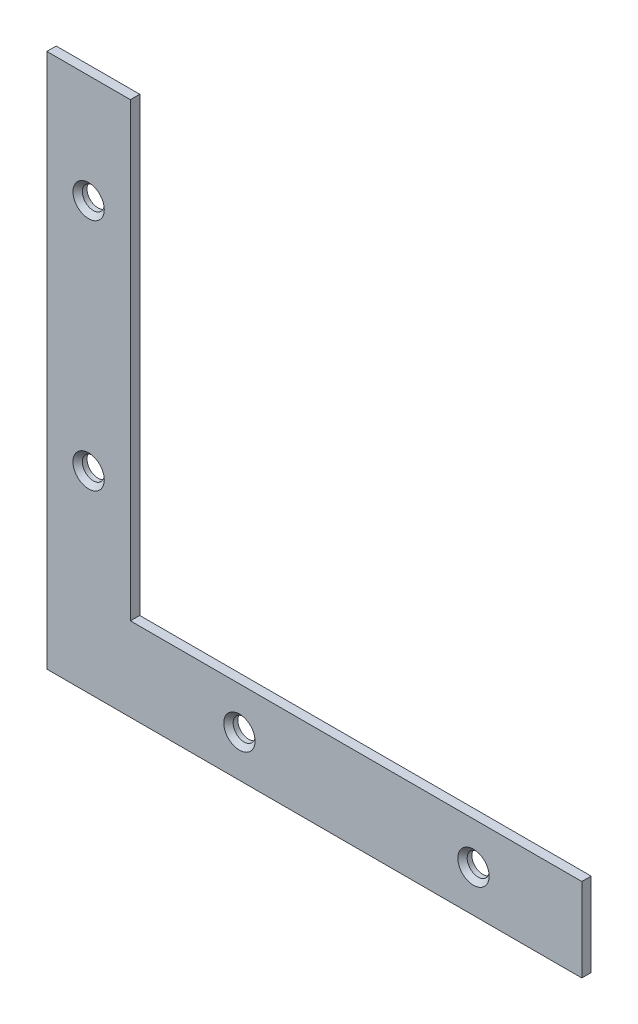
SolidWorks part; units mm, degrees
ref_plane "Front" through (0, 0, 0) normal (0, 0, 1) x (1, 0, 0)
ref_plane "Top" through (0, 0, 0) normal (0, 1, 0) x (1, 0, 0)
ref_plane "Right" through (0, 0, 0) normal (1, 0, 0) x (0, 0, -1)
sketch "Sketch1" plane through (0, 0, 0) normal (0, 0, 1) x (1, 0, 0)
  line L0 (0, 101.6) -> (0, 0)
  line L1 (0, 0) -> (101.6, 0)
  line L2 (101.6, 0) -> (101.6, 15.875)
  line L3 (101.6, 15.875) -> (15.875, 15.875)
  line L4 (15.875, 15.875) -> (15.875, 101.6)
  line L5 (15.875, 101.6) -> (0, 101.6)
  dimension "B" = 15.875
  dimension "A1" = 101.6
extrude "Extrude1" add sketch "Sketch1" along normal mid plane 1.778
sketch "Sketch2" plane through (0, 0, 0) normal (0, 0, 1) x (1, 0, 0)
  line L0 (36.576, 7.9375) -> (-14.224, 7.9375) construction
  line L3 (101.6, 0) -> (101.6, 15.875) construction
  line L4 (36.576, 7.9375) -> (81.026, 7.9375) construction
  circle A0 centre (-14.224, 7.9375) radius 2.0828
  circle A1 centre (36.576, 7.9375) radius 2.0828
  circle A2 centre (81.026, 7.9375) radius 2.0828
  point P9 (58.801, 7.9375)
  point P10 (101.6, 7.9375)
  dimension "Hole Size" = 4.1656
  dimension "Hole Offset V 1" = 0
  dimension "Hole Offset H 1" = 20.574
  dimension "Hole Offset H 2" = 44.45
  dimension "Hole Offset H 3" = 50.8
extrude "Extrude2" cut sketch "Sketch2" against normal through all and the other way through all
chamfer "Chamfer1" distance 0.889 angle 45 2 edges at (83.1088, 7.9375, 0.889) (38.6588, 7.9375, 0.889)
ref_plane "Plane1" through (0, 0, 0) normal (-0.7071, 0.7071, 0) x (0, 0, 1)
mirror "Mirror1" about plane through (0, 0, 0) normal (-0.7071, 0.7071, 0) of "Chamfer1", "Extrude2"
chamfer "Chamfer2" [suppressed] distance 0.889 angle 45
equation "\"D1@Chamfer1\" = \"Thickness@Extrude1\" * .5"
equation "\"D1@Chamfer2\" = \"D1@Chamfer1\""
